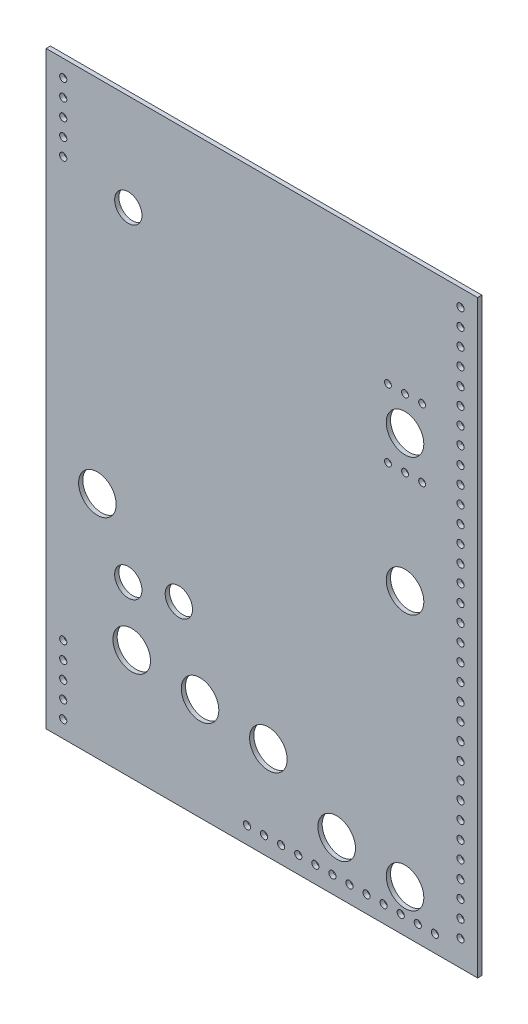
SolidWorks part; units mm, degrees
ref_plane "Front Plane" through (0, 0, 0) normal (0, 0, 1) x (1, 0, 0)
ref_plane "Top Plane" through (0, 0, 0) normal (0, 1, 0) x (1, 0, 0)
ref_plane "Right Plane" through (0, 0, 0) normal (1, 0, 0) x (0, 0, -1)
sketch "Sketch1" plane through (0, 0, 0) normal (0, 0, 1) x (1, 0, 0)
  line L1 (-160.401, 219.075) -> (160.401, 219.075)
  line L2 (-160.401, 219.075) -> (-160.401, -219.075)
  line L3 (-160.401, -219.075) -> (160.401, -219.075)
  line L4 (160.401, 219.075) -> (160.401, -219.075)
  line L5 (-160.401, 219.075) -> (160.401, -219.075) construction
  line L6 (-160.401, -219.075) -> (160.401, 219.075) construction
  point P0 (0, 0)
  dimension "D1" = 438.15
  dimension "D2" = 320.802
extrude "Boss-Extrude1" add sketch "Sketch1" along normal blind 3.175
sketch "Sketch2" plane through (0, 0, 3.175) normal (0, 0, 1) x (1, 0, 0)
  line L0 (160.401, -219.075) -> (106.4458, -219.075) construction
  line L1 (-160.401, -219.075) -> (160.401, -219.075) construction
  line L2 (106.4458, -219.075) -> (106.4458, -187.325) construction
  line L3 (106.4458, -219.075) -> (55.626, -219.075) construction
  line L4 (55.626, -219.075) -> (55.626, -180.975) construction
  line L5 (55.626, -219.075) -> (4.826, -219.075) construction
  line L6 (4.826, -219.075) -> (4.826, -149.225) construction
  line L7 (4.826, -219.075) -> (-45.974, -219.075) construction
  line L8 (-45.974, -219.075) -> (-45.974, -142.875) construction
  line L9 (-45.974, -219.075) -> (-96.774, -219.075) construction
  line L10 (-96.774, -219.075) -> (-96.774, -136.525) construction
  line L11 (106.4458, -187.325) -> (106.4458, 3.175) construction
  circle A0 centre (106.4458, -187.325) radius 13.97
  circle A1 centre (55.626, -180.975) radius 13.97
  circle A2 centre (4.826, -149.225) radius 13.97
  circle A3 centre (-45.974, -142.875) radius 13.97
  circle A4 centre (-96.774, -136.525) radius 13.97
  circle A5 centre (106.4458, 3.175) radius 13.97
  circle A6 centre (106.4458, 104.775) radius 13.97
  circle A7 centre (93.7458, 130.175) radius 2.54
  circle A8 centre (106.4458, 130.175) radius 2.54
  circle A9 centre (119.1458, 130.175) radius 2.54
  circle A10 centre (93.7458, 79.375) radius 2.54
  circle A11 centre (106.4458, 79.375) radius 2.54
  circle A12 centre (119.1458, 79.375) radius 2.54
  point P35 (0, 0)
  point P36 (0, 0)
  dimension "D1" = 69.85
  dimension "D6" = 190.5
  dimension "D7" = 50.8
  dimension "D11" = 27.94
  dimension "D12" = 5.08
  dimension "D2" = 76.2
  dimension "D3" = 82.55
  dimension "D4" = 38.1
  dimension "D5" = 31.75
  dimension "D8" = 25.4
  dimension "D9" = 12.7
  dimension "D10" = 12.7
  dimension "D13" = 101.6
extrude "Cut-Extrude1" cut sketch "Sketch2" against normal blind 3.175
sketch "Sketch3" plane through (0, 0, 3.175) normal (0, 0, 1) x (1, 0, 0)
  line L0 (-160.401, -219.075) -> (-99.314, -219.075) construction
  line L1 (-160.401, -219.075) -> (160.401, -219.075) construction
  line L2 (-99.314, -219.075) -> (-99.314, -94.107) construction
  line L3 (-160.401, -219.075) -> (-61.722, -219.075) construction
  line L4 (-61.722, -219.075) -> (-61.722, -87.757) construction
  line L5 (160.401, 219.075) -> (-160.401, 219.075) construction
  circle A0 centre (-99.314, -94.107) radius 10.16
  circle A1 centre (-61.722, -87.757) radius 10.16
  circle A2 centre (-99.314, 147.193) radius 10.16
  dimension "D2" = 71.882
  dimension "D1" = 124.968
extrude "Cut-Extrude3" cut sketch "Sketch3" against normal blind 3.175 contours A2 | A1 | A0
sketch "Sketch4" plane through (0, 0, 3.175) normal (0, 0, 1) x (1, 0, 0)
  line L0 (-160.401, -219.075) -> (-160.401, -206.4814) construction
  line L1 (-160.401, 219.075) -> (-160.401, -219.075) construction
  line L2 (-160.401, -206.4814) -> (-147.701, -206.4814) construction
  line L3 (-160.401, 0) -> (160.401, 0) construction
  line L4 (160.401, -219.075) -> (160.401, 219.075) construction
  line L5 (0, -219.075) -> (0, 219.075) construction
  line L6 (-160.401, -219.075) -> (160.401, -219.075) construction
  line L7 (160.401, 219.075) -> (-160.401, 219.075) construction
  circle A0 centre (-147.701, -206.4814) radius 2.667
  circle A14 centre (-147.701, -193.7814) radius 2.667
  circle A15 centre (-147.701, -181.0814) radius 2.667
  circle A16 centre (-147.701, -168.3814) radius 2.667
  circle A17 centre (-147.701, -155.6814) radius 2.667
  circle A18 centre (-147.701, 206.4814) radius 2.667
  circle A19 centre (-147.701, 193.7814) radius 2.667
  circle A20 centre (-147.701, 181.0814) radius 2.667
  circle A21 centre (-147.701, 168.3814) radius 2.667
  circle A22 centre (-147.701, 155.6814) radius 2.667
  circle A28 centre (147.701, 155.6814) radius 2.667
  circle A29 centre (147.701, 168.3814) radius 2.667
  circle A30 centre (147.701, 181.0814) radius 2.667
  circle A31 centre (147.701, 193.7814) radius 2.667
  circle A32 centre (147.701, 206.4814) radius 2.667
  circle A61 centre (147.701, 142.9814) radius 2.667
  circle A62 centre (147.701, 130.2814) radius 2.667
  circle A63 centre (147.701, 117.5814) radius 2.667
  circle A64 centre (147.701, 104.8814) radius 2.667
  circle A65 centre (147.701, 92.1814) radius 2.667
  circle A66 centre (147.701, 79.4814) radius 2.667
  circle A67 centre (147.701, 66.7814) radius 2.667
  circle A68 centre (147.701, 54.0814) radius 2.667
  circle A69 centre (147.701, 41.3814) radius 2.667
  circle A70 centre (147.701, 28.6814) radius 2.667
  circle A71 centre (147.701, 15.9814) radius 2.667
  circle A72 centre (147.701, 3.2814) radius 2.667
  circle A73 centre (147.701, -9.4186) radius 2.667
  circle A74 centre (147.701, -22.1186) radius 2.667
  circle A75 centre (147.701, -34.8186) radius 2.667
  circle A76 centre (147.701, -47.5186) radius 2.667
  circle A77 centre (147.701, -60.2186) radius 2.667
  circle A78 centre (147.701, -72.9186) radius 2.667
  circle A79 centre (147.701, -85.6186) radius 2.667
  circle A80 centre (147.701, -98.3186) radius 2.667
  circle A81 centre (147.701, -111.0186) radius 2.667
  circle A82 centre (147.701, -123.7186) radius 2.667
  circle A83 centre (147.701, -136.4186) radius 2.667
  circle A84 centre (147.701, -149.1186) radius 2.667
  circle A85 centre (147.701, -161.8186) radius 2.667
  circle A86 centre (147.701, -174.5186) radius 2.667
  circle A87 centre (147.701, -187.2186) radius 2.667
  circle A88 centre (147.701, -199.9186) radius 2.667
  circle A89 centre (103.251, -206.4814) radius 2.667
  circle A90 centre (115.951, -206.4814) radius 2.667
  circle A91 centre (128.651, -206.4814) radius 2.667
  circle A92 centre (90.551, -206.4814) radius 2.667
  circle A93 centre (65.151, -206.4814) radius 2.667
  circle A94 centre (77.851, -206.4814) radius 2.667
  circle A95 centre (52.451, -206.4814) radius 2.667
  circle A96 centre (39.751, -206.4814) radius 2.667
  circle A97 centre (27.051, -206.4814) radius 2.667
  circle A98 centre (14.351, -206.4814) radius 2.667
  circle A99 centre (1.651, -206.4814) radius 2.667
  circle A100 centre (-11.049, -206.4814) radius 2.667
  point P10 (0, 0)
  dimension "D3" = 12.7
  dimension "D5" = 29
  dimension "D2" = 5
extrude "Cut-Extrude4" cut sketch "Sketch4" against normal blind 3.175
sketch "Sketch5" plane through (0, 0, 3.175) normal (0, 0, 1) x (1, 0, 0)
  line L0 (-160.401, 219.075) -> (-160.401, -219.075) construction
  line L1 (-160.401, -219.075) -> (160.401, -219.075) construction
  circle A0 centre (-122.301, -48.514) radius 13.97
  dimension "D1" = 38.1
  dimension "D2" = 170.561
extrude "Cut-Extrude5" cut sketch "Sketch5" against normal blind 3.175
equation "\"D2@Sketch5\"=6.25+.465"
